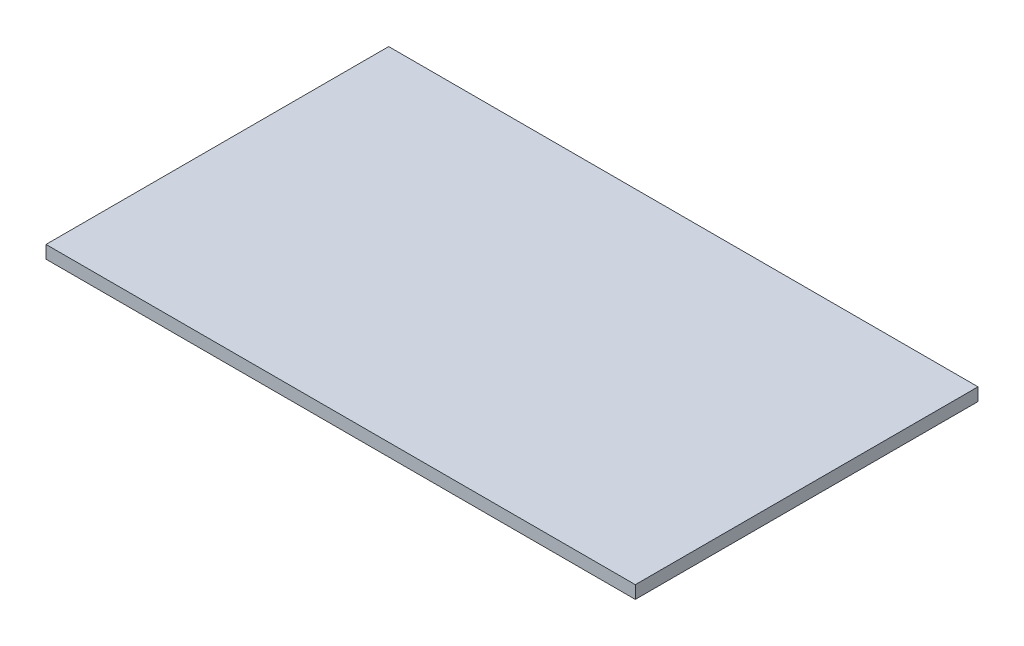
SolidWorks part; units mm, degrees
ref_plane "Front Plane" through (0, 0, 0) normal (0, 0, 1) x (1, 0, 0)
ref_plane "Top Plane" through (0, 0, 0) normal (0, 1, 0) x (1, 0, 0)
ref_plane "Right Plane" through (0, 0, 0) normal (1, 0, 0) x (0, 0, -1)
sketch "Sketch1" plane through (0, 0, 0) normal (0, 1, 0) x (1, 0, 0)
  line L1 (0, 0) -> (1168.4, 0)
  line L2 (0, 0) -> (0, 679.45)
  line L3 (0, 679.45) -> (1168.4, 679.45)
  line L4 (1168.4, 0) -> (1168.4, 679.45)
  dimension "D1" = 1168.4
  dimension "D2" = 679.45
extrude "Boss-Extrude1" add sketch "Sketch1" along normal blind 25.4
